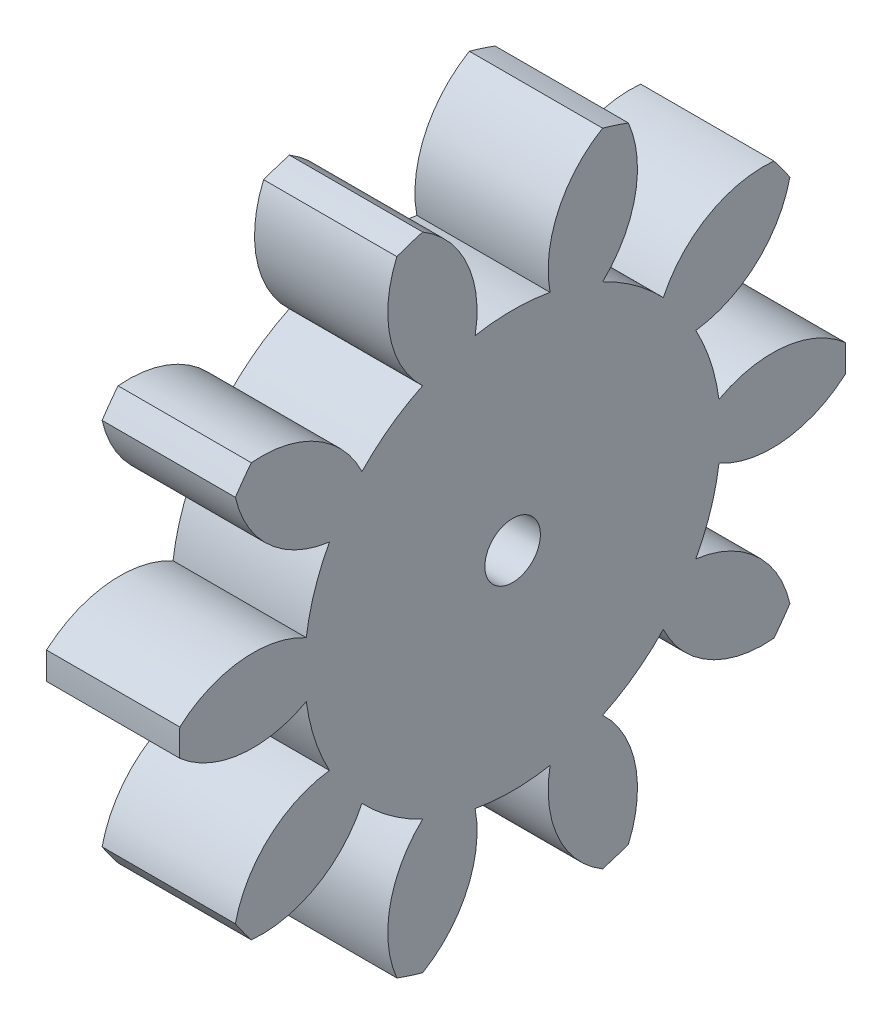
SolidWorks part; units mm, degrees
ref_plane "Plane1" through (0, 0, 0) normal (0, 0, 1) x (1, 0, 0)
ref_plane "Plane2" through (0, 0, 0) normal (0, 1, 0) x (1, 0, 0)
ref_plane "Plane3" through (0, 0, 0) normal (1, 0, 0) x (0, 0, -1)
sketch "HoldingSke" plane through (0, 0, 0) normal (0, 1, 0) x (1, 0, 0)
  line L0 (0, 0) -> (0.197, -0.0347)
  line L1 (-15, 0) -> (100, 0) construction
  line L2 (0, 0) -> (-2.1039, 2.3779)
  line L3 (0, 0) -> (-11.863, 4.5341)
  line L4 (0, 0) -> (8.5048, 1.4996)
  line L5 (0, 0) -> (-46.8476, -17.4728)
  line L6 (0, 0) -> (-9.9476, -6.7116)
  line L7 (-2.1039, 2.3779) -> (8.6586, 51.2059)
  line L8 (-76.2, 54.61) -> (-75.3, 54.61)
  line L9 (-67.7845, 28.3722) -> (-49.3413, 33.142)
  line L10 (-76.2, 71.12) -> (104.1128, 71.12)
  line L11 (0, 0) -> (-12, 0)
  line L12 (-76.2, 101.6) -> (-76.033, 101.6)
  line L13 (24.9733, 27.94) -> (52.9518, 28.4284)
  line L14 (24.9733, 27.94) -> (24.9743, 27.94)
  line L15 (24.9733, 27.94) -> (100.4006, 29.5858)
  line L16 (-63.627, -5) -> (-12.827, -5)
  circle A0 centre (0, 0) radius 2.5
  circle A1 centre (0, 0) radius 18.749
  circle A2 centre (0, 0) radius 37.5
  circle A3 centre (0, 0) radius 2.5
  dimension "MHD" = 37.498
  dimension "Hub_dia" = 75
  dimension "Bore" = 5
  dimension "MBD" = 5
  dimension "Num_teeth" = 10
  dimension "Pitch_radius" = 180.3128
  dimension "Pitch" = 0.2
  dimension "Width" = 12
  dimension "Overall_len" = 50
  dimension "Show_teeth" = 10
  dimension "Thickness" = 12
  dimension "OAL" = 50.0001
  dimension "T_dim" = 0.9
  dimension "Ap" = 14.5
  dimension "H" = 19.05
  dimension "Backlash" = 0.167
  dimension "Addendum_fac" = 1
  dimension "Dedendum_fac" = 1.25
  dimension "Clearance_fac" = 0.25
  dimension "Dedendum_add" = 0.001
  dimension "Module" = 5
sketch "BasProSke" plane through (0, 0, 0) normal (0, 1, 0) x (1, 0, 0)
  line L0 (-10, 0) -> (60, 0) construction
  line L1 (0, 0) -> (0, 30)
  line L2 (0, 0) -> (12, 0)
  line L3 (12, 0) -> (12, 30)
  line L4 (12, 30) -> (0, 30)
  dimension "Diameter" = 60
  dimension "Thickness" = 12
revolve "Base-Revolve" add sketch "BasProSke" angle 360 about L0
sketch "TooCutSke" plane through (0, 0, 0) normal (1, 0, 0) x (0, 0, -1)
  line L1 (0, 0) -> (0, 107) construction
  line L2 (0, 0) -> (-4.2026, 24.6442) construction
  line L3 (0, 0) -> (-15.2881, 47.0521) construction
  line L4 (-4.2026, 24.6442) -> (-7.6441, 23.526) construction
  arc A0 (3.374, 18.4429) -> (-3.374, 18.4429) centre (0, 0) ccw
  arc A1 (8.1303, 28.9037) -> (-8.1303, 28.9037) centre (0, 0) ccw
  circle A2 centre (0, 0) radius 25 construction
  circle A3 centre (0, 0) radius 24.2037 construction
  arc A4 (-3.374, 18.4429) -> (-8.1303, 28.9037) centre (-13.2027, 20.2856) ccw
  arc A5 (8.1303, 28.9037) -> (3.374, 18.4429) centre (13.2027, 20.2856) ccw
  dimension "Root_dia" = 37.498
  dimension "Overcut_dia" = 60.0508
  dimension "Pitch_dia" = 50
  dimension "Base_dia" = 48.4074
  dimension "Flank_rad" = 10
  dimension "Half_ang" = 18
  dimension "Half_CT" = 3.6186
extrude "ToothCut" cut sketch "TooCutSke" along normal through all
fillet "Breaks" [suppressed] radius 0.1
fillet "RootFillets" [suppressed] radius 1.251
pattern_circular "TeethCuts" count 10 every 36 about axis through (-10, 0, 0) along (1, 0, 0) of "ToothCut", "RootFillets", "Breaks"
sketch "HubNeaOneSke" plane through (0, 0, 0) normal (-1, 0, 0) x (0, 0, 1)
  circle A0 centre (0, 0) radius 18.749
  dimension "Diameter" = 37.498
extrude "HubNearOne" [suppressed] add sketch "HubNeaOneSke" along normal blind 38.0001
sketch "HubNeaBotSke" plane through (0, 0, 0) normal (-1, 0, 0) x (0, 0, 1)
  circle A0 centre (0, 0) radius 18.749
  dimension "Diameter" = 37.498
extrude "HubNearBoth" [suppressed] add sketch "HubNeaBotSke" along normal blind 19
ref_plane "FarPln" through (12, 0, 0) normal (1, 0, 0) x (0, 0, -1)
sketch "HubFarSke" plane through (12, 0, 0) normal (1, 0, 0) x (0, 0, -1)
  circle A0 centre (0, 0) radius 18.749
  dimension "Diameter" = 37.498
extrude "HubFar" [suppressed] add sketch "HubFarSke" along normal blind 19
sketch "BorSke" plane through (0, 0, 0) normal (1, 0, 0) x (0, 0, -1)
  circle A0 centre (0, 0) radius 2.5
  dimension "Diameter" = 5
extrude "Bore" cut sketch "BorSke" along normal mid plane 100.0001
sketch "KeySke" plane through (0, 0, 0) normal (1, 0, 0) x (0, 0, -1)
  line L0 (-1, 0) -> (-1, 3.4)
  line L1 (-1, 3.4) -> (1, 3.4)
  line L2 (1, 3.4) -> (1, 0)
  line L3 (0, 0) -> (0, 34) construction
  line L4 (-1, 0) -> (1, 0)
  dimension "Offset" = 3.4
  dimension "Width" = 2
extrude "Keyway" [suppressed] cut sketch "KeySke" along normal mid plane 100.0001
pattern_circular "Keyway2" [suppressed] count 2 every 90 about axis through (-10, 0, 0) along (1, 0, 0)
equation "' \"Module@HoldingSke\" = 6.35"
equation "' \"Num_teeth@HoldingSke\" = 12"
equation "' \"Ap@HoldingSke\" =  20"
equation "' \"Width@HoldingSke\" = 0.5 * 25.4"
equation "' \"Hub_dia@HoldingSke\"= 1 * 25.4"
equation "' \"Overall_len@HoldingSke\" = 1.0 * 25.4"
equation "' \"Bore@HoldingSke\" = 0.75 * 25.4"
equation "' \"T_dim@HoldingSke\" = 0.1 * 25.4"
equation "' \"Width@KeySke\" = 0.25 * 25.4"
equation "' \"Show_teeth@HoldingSke\" = 13"
equation "' \"Backlash@HoldingSke\" = 0.009 * 25.4"
equation "' \"Addendum_fac@HoldingSke\" = 1.0"
equation "' \"Dedendum_fac@HoldingSke\" = 1.25"
equation "' \"Dedendum_add@HoldingSke\" = 0.00005 * 25.4"
equation "' \"Clearance_fac@HoldingSke\" = 0.25"
equation "\"Pitch@HoldingSke\" = 1 / \"Module@HoldingSke\""
equation "\"Overcut_dia@TooCutSke\" = (\"Num_teeth@HoldingSke\" + 2 * \"Addendum_fac@HoldingSke\") / \"Pitch@HoldingSke\" + 0.002 * 25.4"
equation "\"Pitch_dia@TooCutSke\" = \"Num_teeth@HoldingSke\" / \"Pitch@HoldingSke\""
equation "\"Base_dia@TooCutSke\" = \"Num_teeth@HoldingSke\" / \"Pitch@HoldingSke\" * cos((\"Ap@HoldingSke\"  * 3.14159265 / 180))"
equation "\"Root_dia@TooCutSke\" = (\"Num_teeth@HoldingSke\" + 2) / \"Pitch@HoldingSke\" - 2 * (\"Addendum_fac@HoldingSke\" + \"Dedendum_fac@HoldingSke\") / \"Pitch@HoldingSke\" - \"Dedendum_add@HoldingSke\" * 2"
equation "\"Half_ang@TooCutSke\" = 180 / \"Num_teeth@HoldingSke\""
equation "\"Half_CT@TooCutSke\" = \"Num_teeth@HoldingSke\" / \"Pitch@HoldingSke\" * sin((3.14159265 / 2 / \"Num_teeth@HoldingSke\")) / 2 - 7 * \"Backlash@HoldingSke\" / 4"
equation "\"Flank_rad@TooCutSke\" = \"Num_teeth@HoldingSke\" / \"Pitch@HoldingSke\" / 5"
equation "\"Radius@RootFillets\" = \"Clearance_fac@HoldingSke\" / \"Pitch@HoldingSke\" + \"Dedendum_add@HoldingSke\""
equation "\"Break_rad@Breaks\" = 0.02 / \"Pitch@HoldingSke\""
equation "\"Thickness@HoldingSke\" = \"Width@HoldingSke\""
equation "\"OAL@HoldingSke\" = \"Thickness@HoldingSke\""
equation "\"MHD@HoldingSke\" = (\"Num_teeth@HoldingSke\" + 2) / \"Pitch@HoldingSke\" - 2 * (\"Addendum_fac@HoldingSke\" + \"Dedendum_fac@HoldingSke\")  / \"Pitch@HoldingSke\" - \"Dedendum_add@HoldingSke\" * 2"
equation "\"MBD@HoldingSke\" = (\"Num_teeth@HoldingSke\" + 2) / \"Pitch@HoldingSke\" - 2 * (\"Addendum_fac@HoldingSke\" + \"Dedendum_fac@HoldingSke\")  / \"Pitch@HoldingSke\" - \"Dedendum_add@HoldingSke\" * 2 - 0.002 * 25.4"
equation "\"MHD@HoldingSke\" = ((sgn( \"MHD@HoldingSke\" - \"Hub_dia@HoldingSke\" )-1)*( \"MHD@HoldingSke\" - \"Hub_dia@HoldingSke\" ))/-2+ \"Hub_dia@HoldingSke\""
equation "\"MBD@HoldingSke\" = ((sgn( \"MBD@HoldingSke\" - \"Bore@HoldingSke\" )-1)*( \"MBD@HoldingSke\" - \"Bore@HoldingSke\" ))/-2+ \"Bore@HoldingSke\""
equation "\"OAL@HoldingSke\" = ((sgn( \"OAL@HoldingSke\" - \"Overall_len@HoldingSke\" )+1)*( \"OAL@HoldingSke\" - \"Overall_len@HoldingSke\" ))/2 + \"Overall_len@HoldingSke\" + 0.000002 * 25.4"
equation "\"Num_teeth@TeethCuts\" = int( \"Show_teeth@HoldingSke\" ) + 1"
equation "\"Num_teeth@TeethCuts\" = ((sgn( \"Num_teeth@TeethCuts\" - \"Num_teeth@HoldingSke\" )-1)*( \"Num_teeth@TeethCuts\" - \"Num_teeth@HoldingSke\" ))/-2+ \"Num_teeth@HoldingSke\""
equation "\"Num_teeth@TeethCuts\" = ((sgn( \"Num_teeth@TeethCuts\" - 2.0)+1)*( \"Num_teeth@TeethCuts\" - 2.0))/2 +2.0"
equation "\"Angle@TeethCuts\" = 360.0 / \"Num_teeth@HoldingSke\""
equation "\"Diameter@BasProSke\" = (\"Num_teeth@HoldingSke\" + 2 * \"Addendum_fac@HoldingSke\") / \"Pitch@HoldingSke\""
equation "\"Thickness@BasProSke\"  = \"Thickness@HoldingSke\""
equation "' \"Fillet_rad@BasProSke\" =  \"Thickness@HoldingSke\" * 0.05"
equation "\"MHD@HoldingSke\" = ((sgn( \"MHD@HoldingSke\" - \"Root_dia@TooCutSke\" )-1)*( \"MHD@HoldingSke\" - \"Root_dia@TooCutSke\" ))/-2+ \"Root_dia@TooCutSke\""
equation "\"Diameter@HubNeaOneSke\" = \"MHD@HoldingSke\""
equation "\"Length@HubNearOne\" = \"OAL@HoldingSke\" - \"Thickness@BasProSke\""
equation "\"Diameter@HubNeaBotSke\" = \"MHD@HoldingSke\""
equation "\"Length@HubNearBoth\" = ( \"OAL@HoldingSke\" - \"Thickness@BasProSke\" ) / 2.0"
equation "\"Thickness@FarPln\" = \"Thickness@BasProSke\""
equation "\"Diameter@HubFarSke\" = \"MHD@HoldingSke\""
equation "\"Length@HubFar\" = ( \"OAL@HoldingSke\" - \"Thickness@BasProSke\" ) / 2.0"
equation "\"Diameter@BorSke\" = \"MBD@HoldingSke\""
equation "\"D1@Bore\" = \"OAL@HoldingSke\" * 2.0"
equation "\"D1@Keyway\" = \"OAL@HoldingSke\" * 2.0"
equation "\"Offset@KeySke\" = \"T_dim@HoldingSke\" + \"MBD@HoldingSke\" / 2.0"
